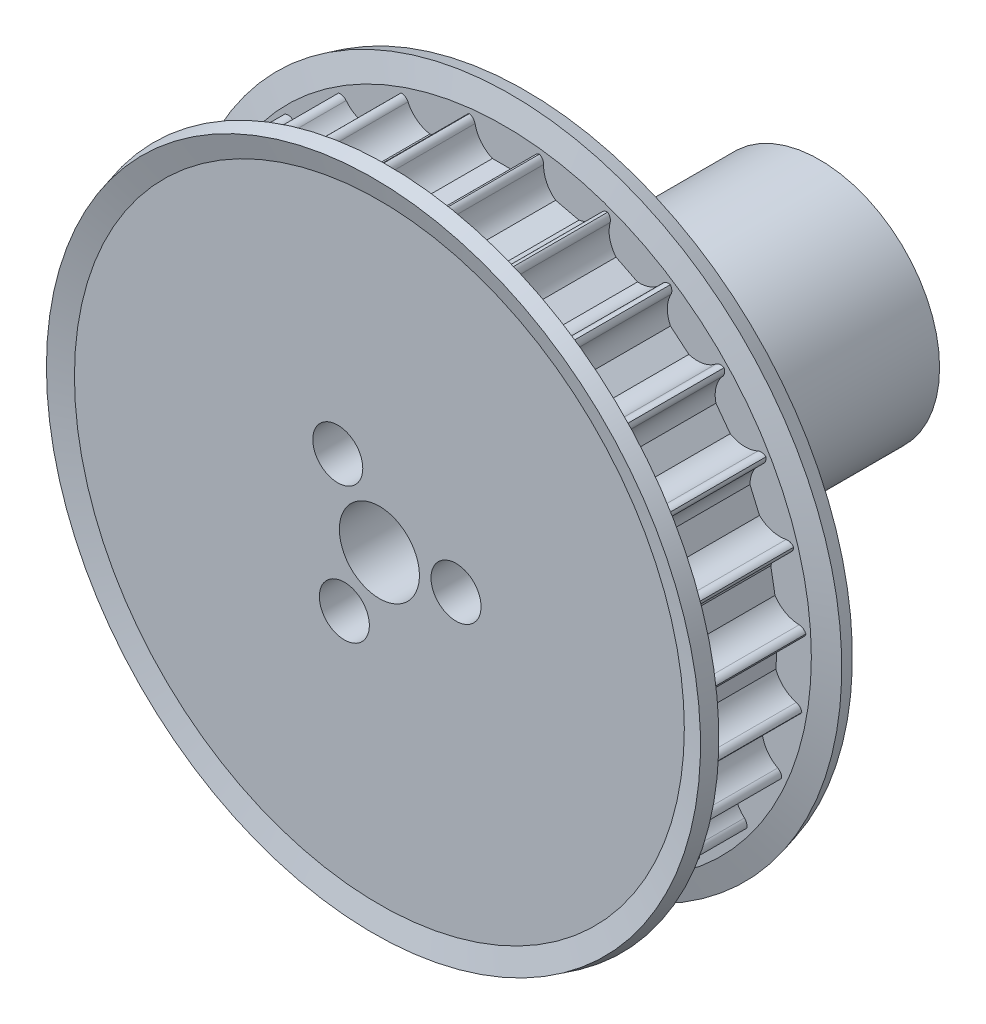
SolidWorks part; units mm, degrees
ref_plane "Front Plane" through (0, 0, 0) normal (0, 0, 1) x (1, 0, 0)
ref_plane "Top Plane" through (0, 0, 0) normal (0, 1, 0) x (1, 0, 0)
ref_plane "Right Plane" through (0, 0, 0) normal (1, 0, 0) x (0, 0, -1)
ref_axis "Axis1" through (0, 0, -88.99) along (0, 0, 1)
sketch "Sketch1" plane through (0, 0, 0) normal (1, 0, 0) x (0, 0, -1)
  line L0 (0, 4) -> (0, 31)
  line L1 (0, 31) -> (14, 31)
  line L2 (14, 31) -> (14, 12)
  line L3 (14, 12) -> (44, 12)
  line L4 (44, 12) -> (44, 4)
  line L5 (44, 4) -> (0, 4)
  line L6 (88.99, 0) -> (-88.99, 0) construction
  dimension "D1" = 30
  dimension "D2" = 31
  dimension "D3" = 12
  dimension "D4" = 14
  dimension "D5" = 4
revolve "Revolve1" add sketch "Sketch1" angle 360 about axis through (0, 0, -88.99) along (0, 0, 1)
sketch "Sketch2" plane through (0, 0, 0) normal (0, 0, 1) x (1, 0, 0)
  line L0 (3.6742, 30) -> (3.75, 30)
  line L1 (-3.75, 30) -> (-3.6742, 30)
  line L2 (-3.75, 30) -> (-3.75, 32)
  line L3 (-3.75, 32) -> (3.75, 32)
  line L4 (3.75, 30) -> (3.75, 32)
  line L5 (-1.199, 27.25) -> (1.199, 27.25)
  arc A0 (-2.9394, 29.4) -> (-1.199, 27.25) centre (0, 30) ccw
  arc A1 (-2.9394, 29.4) -> (-3.6742, 30) centre (-3.6742, 29.25) ccw
  arc A2 (2.9394, 29.4) -> (3.6742, 30) centre (3.6742, 29.25) cw
  arc A3 (1.199, 27.25) -> (2.9394, 29.4) centre (0, 30) ccw
  point P13 (-3, 30)
  point P16 (3, 30)
  dimension "D1" = 3
  dimension "D5" = 0.75
  dimension "D6" = 0.75
  dimension "D2" = 2
  dimension "D3" = 7.5
  dimension "D4" = 30
  dimension "D7" = 2.75
extrude "Cut-Extrude1" cut sketch "Sketch2" against normal through all
pattern_circular "CirPattern1" count 27 over 360 about axis through (0, 0, 0) along (0, 0, 1) of "Cut-Extrude1"
sketch "Sketch3" plane through (0, 0, 0) normal (1, 0, 0) x (0, 0, -1)
  line L0 (0, 29.2854) -> (0, 26.792) construction
  line L1 (0, 27.2415) -> (1.5, 27.2415)
  line L2 (0, 27.2415) -> (0, 30.6805)
  line L3 (0, 30.6805) -> (1.5, 30.6805) construction
  line L4 (1.5, 27.2415) -> (1.5, 30.6805)
  line L5 (1.5, 30.6805) -> (0.0511, 30.2922) construction
  line L6 (1.5, 30.6805) -> (0.8569, 33.0805)
  line L7 (0.0511, 30.2922) -> (-0.592, 32.6922)
  line L8 (0.8569, 33.0805) -> (-0.592, 32.6922)
  line L9 (7, 39.7867) -> (7, -33.9897) construction
  line L10 (12.5, 30.6805) -> (13.9489, 30.2922) construction
  line L11 (14, 30.6805) -> (12.5, 30.6805) construction
  line L12 (13.1431, 33.0805) -> (14.592, 32.6922)
  line L13 (13.9489, 30.2922) -> (14.592, 32.6922)
  line L14 (12.5, 30.6805) -> (13.1431, 33.0805)
  line L15 (12.5, 27.2415) -> (12.5, 30.6805)
  line L16 (14, 27.2415) -> (14, 30.6805)
  line L17 (14, 27.2415) -> (12.5, 27.2415)
  line L18 (0, 28.3642) -> (0, 27.592) construction
  line L19 (0, 27.592) -> (0, 24.8896) construction
  dimension "D1" = 1.5
  dimension "D2" = 1.5
  dimension "D3" = 2.4
  dimension "D4" = 165
  dimension "D5" = 0.7
revolve "Revolve3" add sketch "Sketch3" angle 360 about axis through (0, 0, -88.99) along (0, 0, 1)
sketch "Sketch4" plane through (0, 0, -44) normal (0, 0, -1) x (-1, 0, 0)
  circle A0 centre (-7.6607, 0.3803) radius 2.5
  circle A1 centre (4.1597, 6.4442) radius 2.5
  circle A2 centre (3.501, -6.8245) radius 2.5
  dimension "D1" = 5
  dimension "D3" = 7.6607
  dimension "D2" = 3
extrude "Cut-Extrude2" cut sketch "Sketch4" against normal through all
ref_plane "Plane1" through (0, 0, -7) normal (0, 0, 1) x (1, 0, 0)
sketch "Sketch5" plane through (0, 0, -7) normal (0, 0, 1) x (1, 0, 0)
  circle A0 centre (0, 0) radius 32
  dimension "D1" = 64
